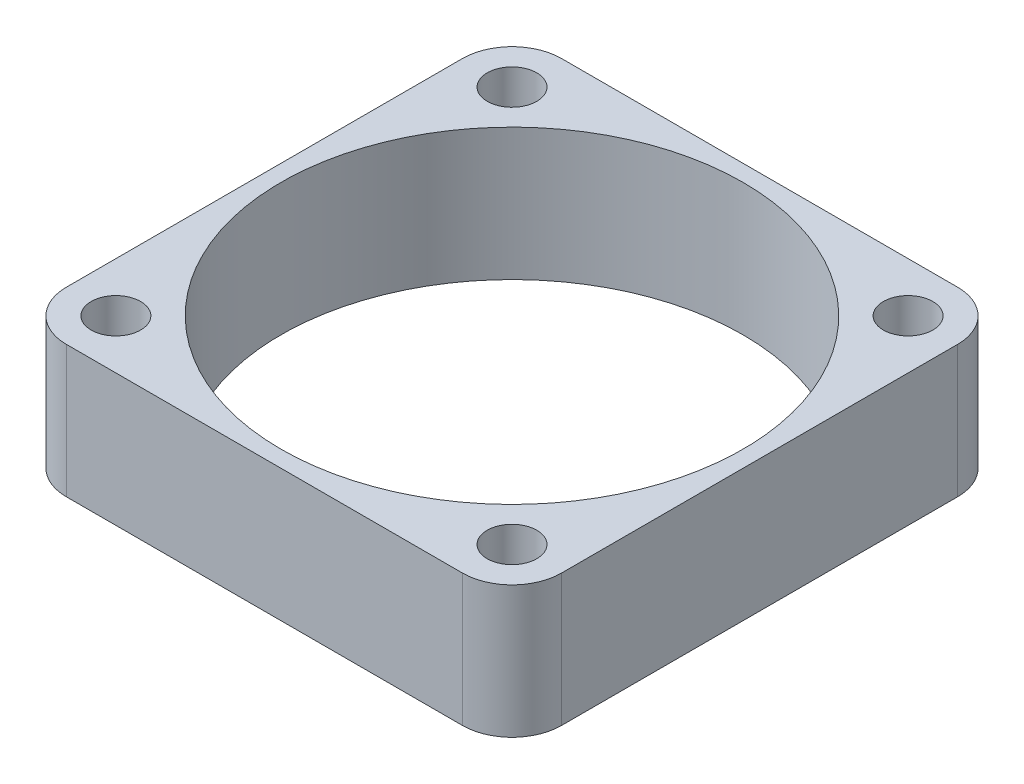
SolidWorks part; units mm, degrees
material "ABS"
ref_plane "Front Plane" through (0, 0, 0) normal (0, 0, 1) x (1, 0, 0)
ref_plane "Top Plane" through (0, 0, 0) normal (0, 1, 0) x (1, 0, 0)
ref_plane "Right Plane" through (0, 0, 0) normal (1, 0, 0) x (0, 0, -1)
sketch "Sketch1" plane through (0, 0, 0) normal (0, 1, 0) x (1, 0, 0)
  line L1 (-15, -15) -> (15, -15)
  line L2 (-15, -15) -> (-15, 15)
  line L3 (-15, 15) -> (15, 15)
  line L4 (15, -15) -> (15, 15)
  line L5 (-15, -15) -> (15, 15) construction
  line L6 (-15, 15) -> (15, -15) construction
  line L12 (-39, -15) -> (-39, 15) [skipped]
  line L13 (-39, -39) -> (-39, -9) [skipped]
  line L14 (-15, -39) -> (-15, -9) [skipped]
  line L15 (-39, -9) -> (-9, -9) [skipped]
  line L16 (-15, -9) -> (15, -9) [skipped]
  line L17 (-39, 15) -> (-9, 15) [skipped]
  circle A0 centre (12, 12) radius 1.5
  circle A1 centre (-12, 12) radius 1.5
  circle A2 centre (-12, -12) radius 1.5
  circle A3 centre (12, -12) radius 1.5
  circle A4 centre (0, 0) radius 14
  point P0 (0, 0)
  dimension "D9" = 3
  dimension "D10" = 28
  dimension "D1" = 30
  dimension "D2" = 30
  dimension "D4" = 3
  dimension "D6" = 24
  dimension "D7" = 24
  dimension "D8" = 3
  dimension "D5" = 2
  dimension "D3" = 2
extrude "Boss-Extrude1" add sketch "Sketch1" along normal blind 8
fillet "Fillet1" radius 3 4 edges at (-15, 4, -15) (15, 4, -15) (15, 4, 15) (-15, 4, 15)
